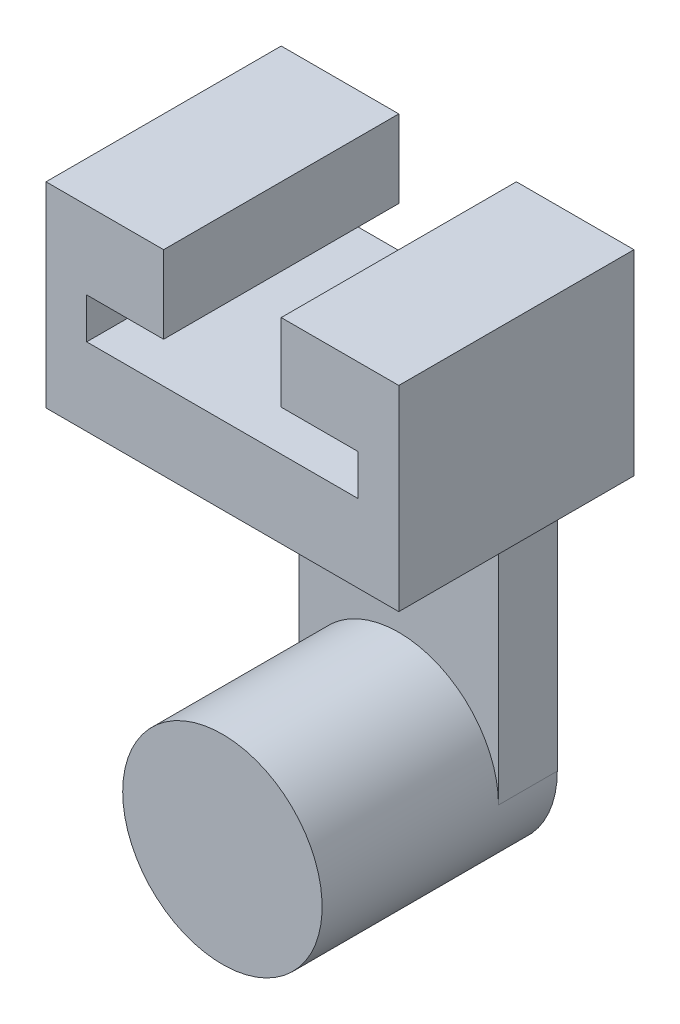
SolidWorks part; units mm, degrees
material "6061-T6 (SS)"
ref_plane "Front Plane" through (0, 0, 0) normal (0, 0, 1) x (1, 0, 0)
ref_plane "Top Plane" through (0, 0, 0) normal (0, 1, 0) x (1, 0, 0)
ref_plane "Right Plane" through (0, 0, 0) normal (1, 0, 0) x (0, 0, -1)
sketch "Sketch1" plane through (0, 0, 0) normal (0, 0, 1) x (1, 0, 0)
  line L1 (0, 0) -> (-38.1, 0)
  line L2 (0, 0) -> (0, 8.382)
  line L3 (0, 8.382) -> (-38.1, 8.382)
  line L4 (-38.1, 0) -> (-38.1, 8.382)
  point P18 (0, 0)
  dimension "D2" = 8.382
  dimension "D1" = 38.1
extrude "Boss-Extrude1" add sketch "Sketch1" along normal blind 25.4
sketch "Sketch2" plane through (0, 0, 25.4) normal (0, 0, 1) x (1, 0, 0)
  line L1 (-38.1, 8.382) -> (-33.7058, 8.382)
  line L2 (-38.1, 8.382) -> (-38.1, 12.7762)
  line L3 (-38.1, 12.7762) -> (-33.7058, 12.7762)
  line L4 (-33.7058, 8.382) -> (-33.7058, 12.7762)
  line L5 (0, 8.382) -> (-4.3942, 8.382)
  line L6 (0, 8.382) -> (0, 12.7762)
  line L7 (0, 12.7762) -> (-4.3942, 12.7762)
  line L8 (-4.3942, 8.382) -> (-4.3942, 12.7762)
  dimension "D1" = 4.3942
extrude "Boss-Extrude2" add sketch "Sketch2" against normal blind 25.4
sketch "Sketch3" plane through (0, 0, 25.4) normal (0, 0, 1) x (1, 0, 0)
  line L1 (-38.1, 12.7762) -> (-25.4, 12.7762)
  line L2 (-38.1, 12.7762) -> (-38.1, 21.1582)
  line L3 (-38.1, 21.1582) -> (-25.4, 21.1582)
  line L4 (-25.4, 12.7762) -> (-25.4, 21.1582)
  line L5 (0, 12.7762) -> (-12.7, 12.7762)
  line L6 (0, 12.7762) -> (0, 21.1582)
  line L7 (0, 21.1582) -> (-12.7, 21.1582)
  line L8 (-12.7, 12.7762) -> (-12.7, 21.1582)
  dimension "D1" = 12.7
  dimension "D2" = 8.382
extrude "Boss-Extrude3" add sketch "Sketch3" against normal blind 25.4
sketch "Sketch4" plane through (0, 0, 0) normal (0, 0, -1) x (-1, 0, 0)
  line L2 (29.8196, 0) -> (29.8196, -31.75)
  line L3 (8.2804, 0) -> (8.2804, -31.75)
  line L5 (8.2804, 0) -> (29.8196, 0)
  line L6 (8.2804, -31.75) -> (29.8196, -31.75)
  dimension "D1" = 21.5392
  dimension "D2" = 31.75
  dimension "D3" = 8.2804
  dimension "D4" = 8.2804
extrude "Boss-Extrude4" add sketch "Sketch4" against normal blind 6.35 separate body
sketch "Sketch5" plane through (0, 0, 0) normal (0, 0, -1) x (-1, 0, 0)
  line L0 (8.2804, -31.75) -> (29.8196, -31.75) construction
  line L1 (38.1, 0) -> (0, 0) construction
  circle A0 centre (19.05, -31.75) radius 10.7696
  point P6 (19.05, 0)
  dimension "D2" = 21.5392
  dimension "D1" = 31.75
extrude "Boss-Extrude5" add sketch "Sketch5" against normal blind 25.4
equation "\"A_Diameter\"= 0.848in"
equation "\"Link_Length\"= 1.25in"
equation "\"D2@Sketch5\"=\"A_Diameter\""
equation "\"D2@Sketch4\"=\"Link_Length\""
equation "\"E_Thick\" = 0.33in'E_"
equation "\"E_width\"= 0.5in"
equation "\"D2@Sketch3\"=\"E_Thick\""
equation "\"D1@Sketch3\"=\"E_width\""
equation "\"C_Length\"= 1.50in"
equation "\"C_width\"= 0.33in"
equation "\"D1@Sketch1\"=\"C_Length\""
equation "\"D2@Sketch1\"=\"C_width\""
equation "\"C_Thick\"= 1.00in"
equation "\"D1@Boss-Extrude1\"=\"C_Thick\""
equation "\"D1@Boss-Extrude2\"=\"C_Thick\""
equation "\"D1@Boss-Extrude3\"=\"C_Thick\""
equation "\"D1@Boss-Extrude5\"=\"C_Thick\""
